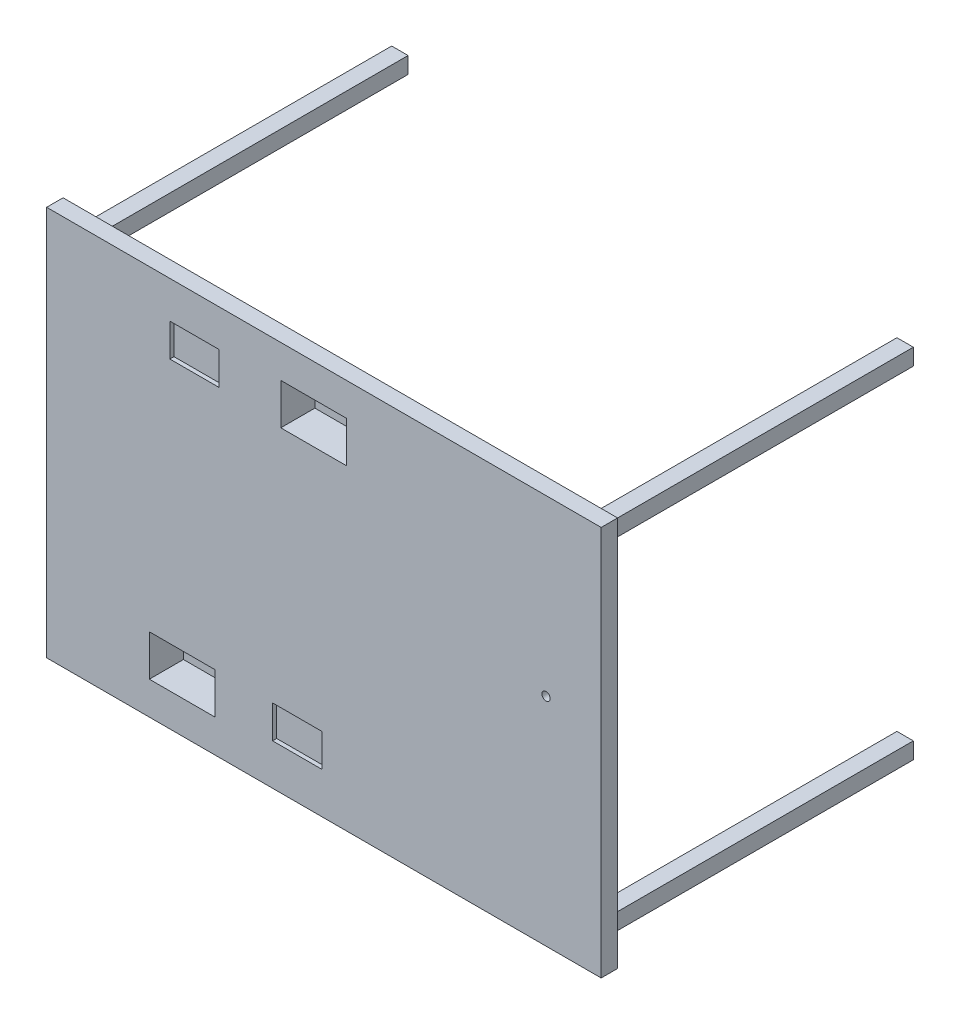
SolidWorks part; units mm, degrees
ref_plane "Plan de face" through (0, 0, 0) normal (0, 0, 1) x (1, 0, 0)
ref_plane "Plan de dessus" through (0, 0, 0) normal (0, 1, 0) x (1, 0, 0)
ref_plane "Plan de droite" through (0, 0, 0) normal (1, 0, 0) x (0, 0, -1)
sketch "Esquisse1" plane through (0, 0, 0) normal (0, 0, 1) x (1, 0, 0)
  line L0 (40, -40) -> (1310, -40)
  line L1 (0, 0) -> (1350, 0)
  line L2 (0, 0) -> (0, -950)
  line L3 (0, -950) -> (1350, -950)
  line L4 (1350, 0) -> (1350, -950)
  line L5 (1310, -40) -> (1310, -910)
  line L6 (40, -910) -> (1310, -910)
  line L7 (40, -40) -> (40, -910)
  dimension "D1" = 1350
  dimension "D2" = 950
  dimension "D3" = 40
extrude "Boss.-Extru.1" add sketch "Esquisse1" along normal blind 40
sketch "Esquisse2" plane through (0, 0, 0) normal (0, 0, -1) x (-1, 0, 0)
  line L0 (-1310, -40) -> (-40, -40) construction
  line L1 (-1310, -40) -> (-1270, -40)
  line L2 (-1310, -40) -> (-1310, -80)
  line L3 (-1310, -80) -> (-1270, -80)
  line L4 (-1270, -40) -> (-1270, -80)
  line L5 (-40, -40) -> (-80, -40)
  line L6 (-40, -40) -> (-40, -80)
  line L7 (-40, -80) -> (-80, -80)
  line L8 (-80, -40) -> (-80, -80)
  line L9 (-40, -40) -> (-40, -910) construction
  line L11 (-40, -910) -> (-80, -910)
  line L12 (-40, -910) -> (-40, -870)
  line L13 (-40, -870) -> (-80, -870)
  line L14 (-80, -910) -> (-80, -870)
  line L15 (-1310, -910) -> (-1270, -910)
  line L16 (-1310, -910) -> (-1310, -870)
  line L17 (-1310, -870) -> (-1270, -870)
  line L18 (-1270, -910) -> (-1270, -870)
  dimension "D1" = 40
  dimension "D2" = 40
  dimension "D3" = 40
  dimension "D4" = 40
  dimension "D5" = 40
  dimension "D6" = 40
  dimension "D7" = 40
  dimension "D8" = 40
extrude "Boss.-Extru.2" add sketch "Esquisse2" along normal blind 760 and the other way blind 22 separate body
sketch "Esquisse3" plane through (0, 0, 22) normal (0, 0, 1) x (1, 0, 0)
  line L1 (40, -40) -> (1310, -40)
  line L2 (40, -40) -> (40, -910)
  line L3 (40, -910) -> (1310, -910)
  line L4 (1310, -40) -> (1310, -910)
extrude "Boss.-Extru.3" add sketch "Esquisse3" along normal blind 18 separate body
sketch "Esquisse4" plane through (0, 0, 40) normal (0, 0, 1) x (1, 0, 0)
  line L0 (40, -40) -> (40, -910) construction
  line L1 (250, -770) -> (410, -770)
  line L2 (250, -770) -> (250, -870)
  line L3 (250, -870) -> (410, -870)
  line L4 (410, -770) -> (410, -870)
  line L5 (250, -770) -> (410, -870) construction
  line L6 (250, -870) -> (410, -770) construction
  line L7 (570, -80) -> (730, -80)
  line L8 (570, -80) -> (570, -180)
  line L9 (570, -180) -> (730, -180)
  line L10 (730, -80) -> (730, -180)
  line L11 (570, -80) -> (730, -180) construction
  line L12 (570, -180) -> (730, -80) construction
  line L13 (0, 0) -> (0, -950) construction
  line L14 (0, -950) -> (1350, -950) construction
  line L15 (1350, 0) -> (0, 0) construction
  point P0 (330, -820)
  point P5 (650, -130)
  dimension "D1" = 100
  dimension "D2" = 160
  dimension "D3" = 160
  dimension "D4" = 100
  dimension "D5" = 530
  dimension "D6" = 250
  dimension "D7" = 80
  dimension "D8" = 80
extrude "Enlèv. mat.-Extru.1" cut sketch "Esquisse4" against normal through all
sketch "Esquisse5" plane through (0, 0, 22) normal (0, 0, -1) x (-1, 0, 0)
  line L0 (-420, -760) -> (-420, -880)
  line L1 (-730, -80) -> (-570, -80)
  line L2 (-730, -80) -> (-730, -180)
  line L3 (-730, -180) -> (-570, -180)
  line L4 (-570, -80) -> (-570, -180)
  line L5 (-410, -770) -> (-250, -770)
  line L6 (-410, -770) -> (-410, -870)
  line L7 (-410, -870) -> (-250, -870)
  line L8 (-250, -770) -> (-250, -870)
  line L9 (-420, -880) -> (-240, -880)
  line L10 (-240, -760) -> (-240, -880)
  line L11 (-420, -760) -> (-240, -760)
  line L12 (-740, -70) -> (-560, -70)
  line L13 (-560, -70) -> (-560, -190)
  line L14 (-740, -190) -> (-560, -190)
  line L15 (-740, -70) -> (-740, -190)
  dimension "D1" = 10
extrude "Boss.-Extru.4" add sketch "Esquisse5" along normal blind 65
sketch "Esquisse6" plane through (0, 0, -43) normal (0, 0, -1) x (-1, 0, 0)
  line L1 (-740, -70) -> (-560, -70)
  line L2 (-740, -70) -> (-740, -190)
  line L3 (-740, -190) -> (-560, -190)
  line L4 (-560, -70) -> (-560, -190)
  line L5 (-420, -760) -> (-240, -760)
  line L6 (-420, -760) -> (-420, -880)
  line L7 (-420, -880) -> (-240, -880)
  line L8 (-240, -760) -> (-240, -880)
extrude "Boss.-Extru.5" add sketch "Esquisse6" along normal blind 10
sketch "Esquisse7" plane through (0, 0, 40) normal (0, 0, 1) x (1, 0, 0)
  line L0 (1350, 0) -> (0, 0) construction
  line L1 (300, -90) -> (420, -90)
  line L2 (300, -90) -> (300, -170)
  line L3 (300, -170) -> (420, -170)
  line L4 (420, -90) -> (420, -170)
  line L5 (550, -850) -> (670, -850)
  line L6 (550, -850) -> (550, -770)
  line L7 (550, -770) -> (670, -770)
  line L8 (670, -850) -> (670, -770)
  line L9 (0, 0) -> (0, -950) construction
  line L10 (1350, -950) -> (1350, 0) construction
  line L11 (0, -950) -> (1350, -950) construction
  dimension "D1" = 120
  dimension "D2" = 80
  dimension "D3" = 120
  dimension "D4" = 80
  dimension "D5" = 90
  dimension "D6" = 300
  dimension "D7" = 680
  dimension "D8" = 100
extrude "Enlèv. mat.-Extru.2" cut sketch "Esquisse7" against normal blind 10
sketch "Esquisse8" plane through (0, 0, 22) normal (0, 0, -1) x (-1, 0, 0)
  line L0 (0, -950) -> (-1350, -950) construction
  circle A0 centre (-1215.8011, -423) radius 10
  dimension "D1" = 20
  dimension "D2" = 527
extrude "Enlèv. mat.-Extru.3" cut sketch "Esquisse8" against normal through all
